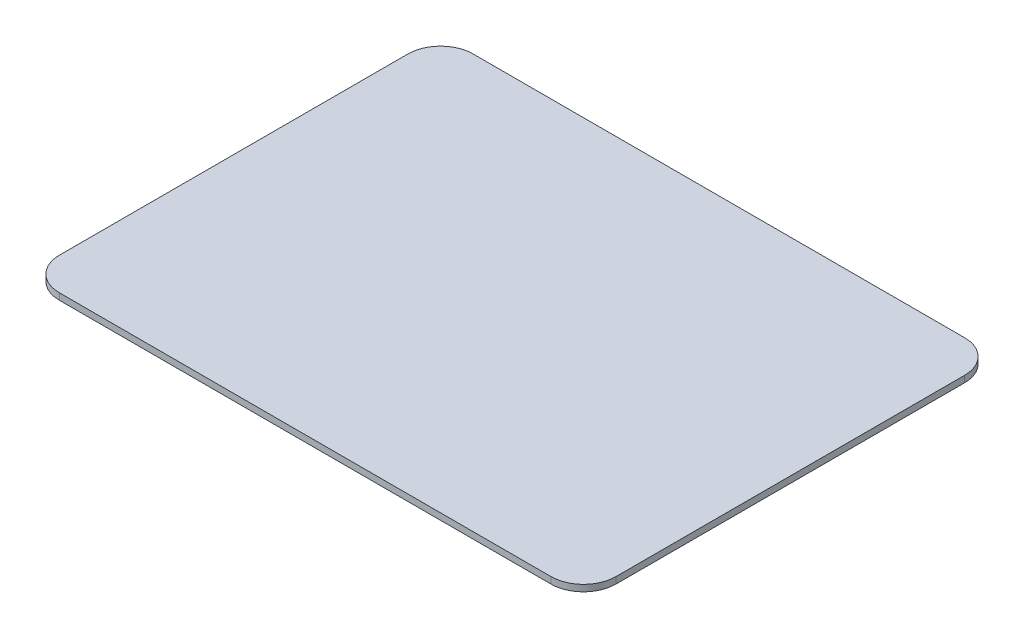
SolidWorks part; units mm, degrees
ref_plane "前视基准面" through (0, 0, 0) normal (0, 0, 1) x (1, 0, 0)
ref_plane "上视基准面" through (0, 0, 0) normal (0, 1, 0) x (1, 0, 0)
ref_plane "右视基准面" through (0, 0, 0) normal (1, 0, 0) x (0, 0, -1)
sketch "草图1" plane through (0, 0, 0) normal (0, 1, 0) x (1, 0, 0)
  line L7 (20.9359, 141.2761) -> (277.3018, 141.2761)
  line L8 (20.9359, 141.2761) -> (20.9359, -49.256)
  line L9 (20.9359, -49.256) -> (277.3018, -49.256)
  line L10 (277.3018, 141.2761) -> (277.3018, -49.256)
extrude "凸台-拉伸1" add sketch "草图1" along normal blind 3
fillet "圆角1" radius 15 4 edges at (277.3018, 1.5, 49.256) (277.3018, 1.5, -141.2761) (20.9359, 1.5, -141.2761) (20.9359, 1.5, 49.256)
